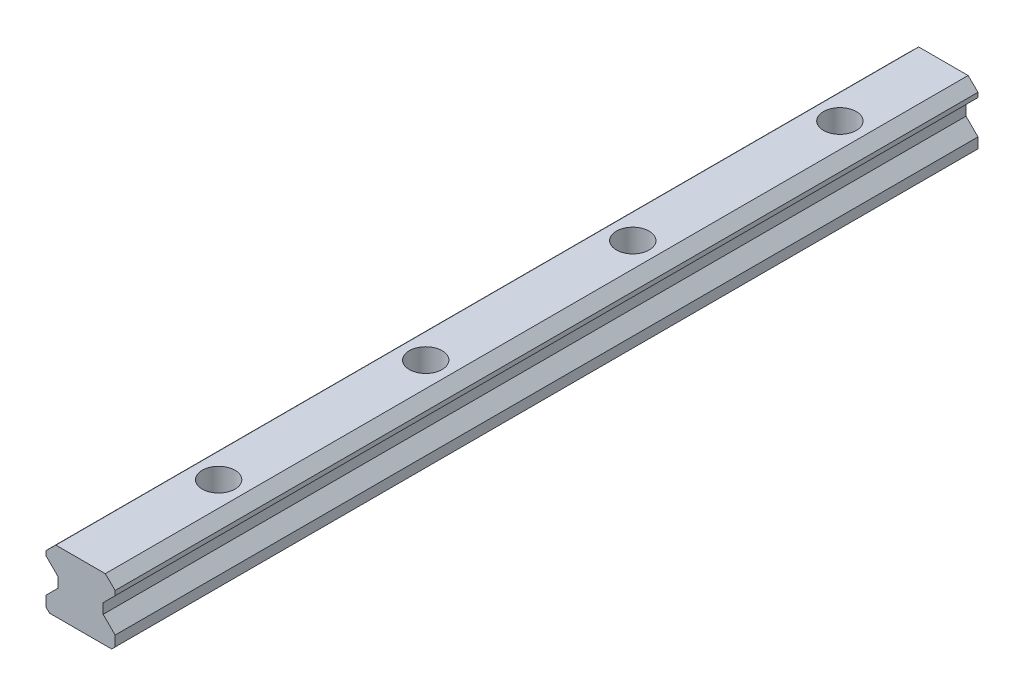
SolidWorks part; units mm, degrees
ref_plane "Front Plane" through (0, 0, 0) normal (0, 0, 1) x (1, 0, 0)
ref_plane "Top Plane" through (0, 0, 0) normal (0, 1, 0) x (1, 0, 0)
ref_plane "Right Plane" through (0, 0, 0) normal (1, 0, 0) x (0, 0, -1)
sketch "Sketch1" plane through (0, 0, 0) normal (0, 0, 1) x (1, 0, 0)
  line L0 (0, 0) -> (0, 18) construction
  line L1 (-10.0182, 0) -> (10.0182, 0)
  line L2 (10.0182, 0) -> (10.0182, 4.0182)
  line L3 (10.0182, 4.0182) -> (6.55, 7.4865)
  line L4 (6.55, 7.4865) -> (6.55, 10.4165)
  line L5 (6.55, 10.4165) -> (10.0182, 13.8847)
  line L6 (10.0182, 13.8847) -> (10.0182, 15.2147)
  line L7 (10.0182, 15.2147) -> (7.16, 18)
  line L8 (7.16, 18) -> (-7.16, 18)
  line L9 (10.0182, 1.0182) -> (9, 0)
  line L10 (-10.0182, 1.0182) -> (-9, 0)
  line L11 (-10.0182, 0) -> (-10.0182, 4.0182)
  line L12 (-10.0182, 4.0182) -> (-6.55, 7.4865)
  line L13 (-6.55, 7.4865) -> (-6.55, 10.4165)
  line L14 (-6.55, 10.4165) -> (-10.0182, 13.8847)
  line L15 (-10.0182, 13.8847) -> (-10.0182, 15.2147)
  line L16 (-10.0182, 15.2147) -> (-7.16, 18)
  dimension "D1" = 7.16
  dimension "D2" = 135
  dimension "D3" = 135
  dimension "D4" = 2.93
  dimension "D5" = 1.33
  dimension "D6" = 1.44
  dimension "D7" = 45
  dimension "D8" = 9
  dimension "D9" = 6.55
  dimension "D10" = 3
  dimension "D11" = 18
extrude "Boss-Extrude1" add sketch "Sketch1" along normal blind 250 contours L0 L1 L9 L2 L3 L4 L5 L6 L7 L8 | L1 L0 L8 L16 L15 L14 L13 L12 L11 L10
sketch "Sketch2" plane through (0, 18, 0) normal (0, 1, 0) x (1, 0, 0)
  line L0 (0, 0) -> (0, -40.3789) construction
  line L1 (7.16, 0) -> (-7.16, 0) construction
  circle A0 centre (0, -30) radius 4.75
  dimension "D2" = 9.5
  dimension "D1" = 30
hole_wizard "Hole1" positions "3DSketch1" profile "Sketch4" legacy end condition through all
sketch3d "3DSketch1"
  point P6 (0, 18, 30)
sketch "Sketch4" plane through (0, 18, 30) normal (1, 0, 0) x (0, 0, 1)
  line L0 (0, 0) -> (0, 19.6524)
  line L1 (0, 19.6524) -> (2.75, 18)
  line L2 (2.75, 18) -> (2.75, 8.5)
  line L3 (2.75, 8.5) -> (4.75, 8.5)
  line L4 (4.75, 0) -> (0, 0)
  line L5 (0, -11.3109) -> (0, 121.1557) construction
  line L6 (0, 19.6524) -> (-2.75, 18) construction
  line L7 (4.75, 8.5) -> (4.75, 0)
  dimension "Depth" = 18
  dimension "Drill Angle" = 118
  dimension "Diameter" = 5.5
  dimension "C-Bore Diameter" = 9.5
  dimension "C-Bore Depth" = 8.5
pattern_linear "LPattern2" count 4 spacing 60 along (0, 0, 1) of "Hole1"
equation "\"lenght\"= 250"
equation "\"D1@Boss-Extrude1\"=\"lenght\""
equation "\"D1@LPattern2\"=(\"lenght\"/60)"
